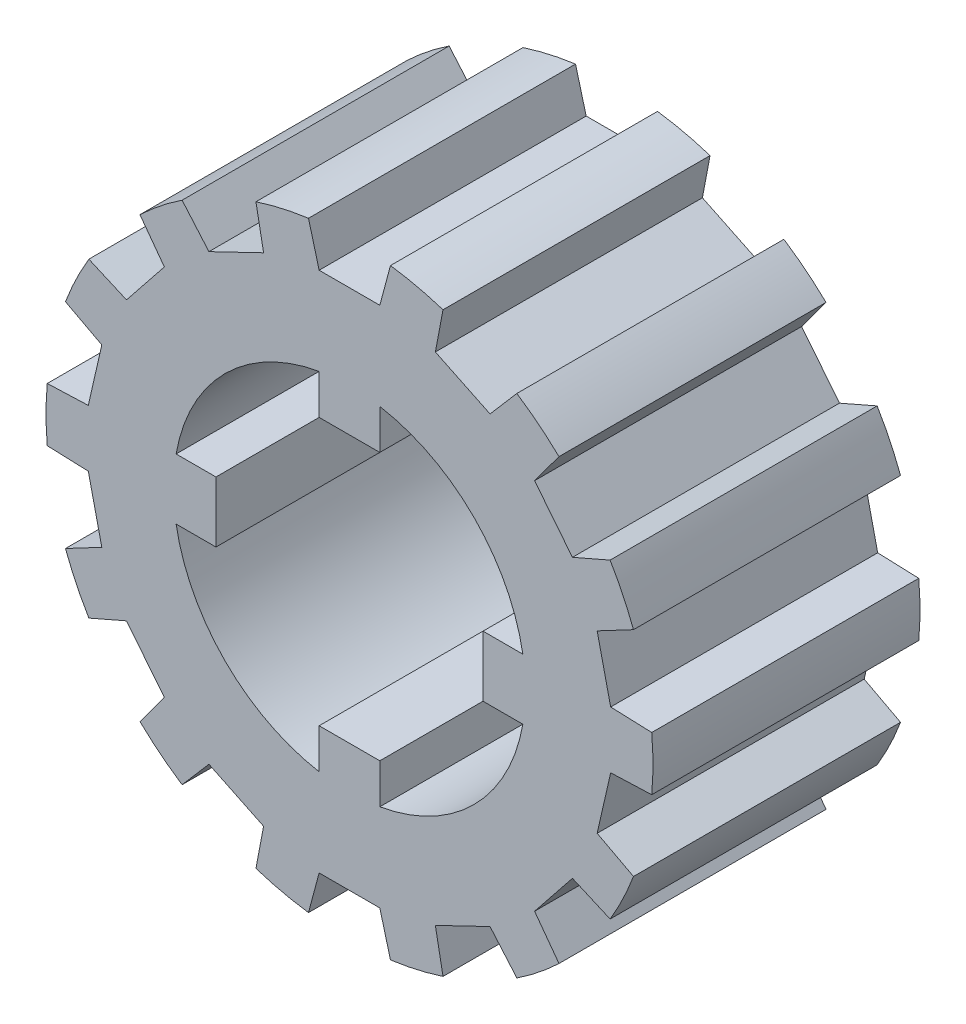
SolidWorks part; units mm, degrees
ref_plane "Plano frontal" through (0, 0, 0) normal (0, 0, 1) x (1, 0, 0)
ref_plane "Plano superior" through (0, 0, 0) normal (0, 1, 0) x (1, 0, 0)
ref_plane "Plano direito" through (0, 0, 0) normal (1, 0, 0) x (0, 0, -1)
sketch "Esboço1" plane through (0, 0, 0) normal (0, 0, 1) x (1, 0, 0)
  circle A0 centre (0, 0) radius 25
  dimension "D1" = 50
extrude "Ressalto-extrusão1" add sketch "Esboço1" along normal blind 22
sketch "Esboço2" plane through (0, 0, 22) normal (0, 0, 1) x (1, 0, 0)
  line L0 (0, 0) -> (11, 0) construction
  line L1 (-2.5, -11) -> (2.5, -11)
  line L2 (-2.5, -11) -> (-2.5, -14.2829)
  line L3 (11, 2.5) -> (14.2829, 2.5)
  line L4 (2.5, -11) -> (2.5, -14.2829)
  line L5 (11, 2.5) -> (11, -2.5)
  line L6 (2.5, 11) -> (2.5, 14.2829)
  line L7 (-2.5, 11) -> (2.5, 11)
  line L8 (-2.5, 11) -> (-2.5, 14.2829)
  line L9 (11, -2.5) -> (14.2829, -2.5)
  line L10 (0, 8.0588) -> (0, 0) construction
  line L11 (-11, -2.5) -> (-14.2829, -2.5)
  line L12 (-11, 2.5) -> (-11, -2.5)
  line L13 (-11, 2.5) -> (-14.2829, 2.5)
  arc A0 (2.5, -14.2829) -> (14.2829, -2.5) centre (0, 0) ccw
  arc A1 (-2.5, 14.2829) -> (-14.2829, 2.5) centre (0, 0) ccw
  arc A2 (14.2829, 2.5) -> (2.5, 14.2829) centre (0, 0) ccw
  arc A3 (-14.2829, -2.5) -> (-2.5, -14.2829) centre (0, 0) ccw
  dimension "D1" = 29
  dimension "D2" = 5
  dimension "D3" = 11
  dimension "D4" = 5
  dimension "D5" = 11
extrude "Corte-extrusão1" cut sketch "Esboço2" against normal blind 32 and the other way blind 24
sketch "Esboço3" plane through (0, 0, 22) normal (0, 0, 1) x (1, 0, 0)
  line L0 (0, -21.5) -> (0, 0) construction
  line L1 (-3.3764, -24.7709) -> (0.8909, -26.391)
  line L2 (0.8909, -26.391) -> (3.3764, -24.7709)
  line L3 (-2.5, -21.5) -> (2.5, -21.5)
  line L5 (-2.5, -21.5) -> (-3.3764, -24.7709)
  line L6 (2.5, -21.5) -> (3.3764, -24.7709)
  circle A0 centre (0, 0) radius 25 construction
  dimension "D3" = 105
  dimension "D1" = 21.5
  dimension "D2" = 5
  dimension "D4" = 105
extrude "Corte-extrusão2" cut sketch "Esboço3" against normal blind 32
pattern_circular "PadrãoCircular1" count 14 over 360 about axis through (0, 0, 0) along (0, 0, 1) of "Corte-extrusão2"
